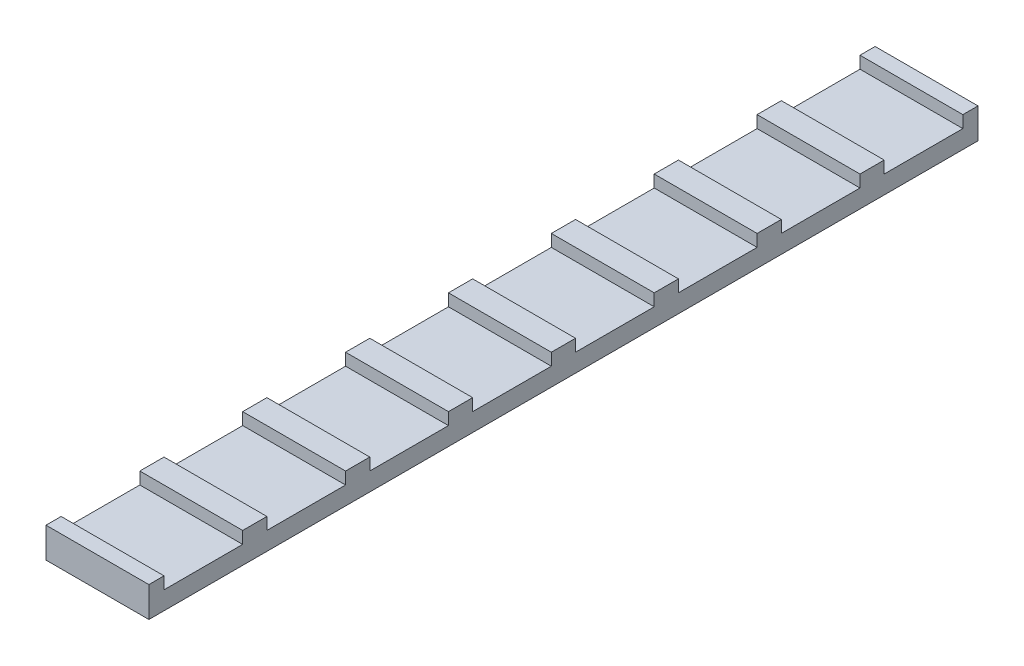
SolidWorks part; units mm, degrees
ref_plane "Front Plane" through (0, 0, 0) normal (0, 0, 1) x (1, 0, 0)
ref_plane "Top Plane" through (0, 0, 0) normal (0, 1, 0) x (1, 0, 0)
ref_plane "Right Plane" through (0, 0, 0) normal (1, 0, 0) x (0, 0, -1)
sketch "Sketch1" plane through (0, 0, 0) normal (0, 1, 0) x (1, 0, 0)
  line L1 (-8.5, -68.5) -> (8.5, -68.5)
  line L2 (-8.5, -68.5) -> (-8.5, 68.5)
  line L3 (-8.5, 68.5) -> (8.5, 68.5)
  line L4 (8.5, -68.5) -> (8.5, 68.5)
  line L5 (-8.5, -68.5) -> (8.5, 68.5) construction
  line L6 (-8.5, 68.5) -> (8.5, -68.5) construction
  point P0 (0, 0)
  dimension "D1" = 137
  dimension "D2" = 17
extrude "Boss-Extrude1" add sketch "Sketch1" along normal blind 5
sketch "Sketch2" plane through (0, 5, 0) normal (0, 1, 0) x (1, 0, 0)
  line L0 (-8.5, 68.5) -> (-8.5, -68.5) construction
  line L1 (-8.5, 66) -> (8.5, 66)
  line L2 (-8.5, 66) -> (-8.5, 53)
  line L3 (-8.5, 53) -> (8.5, 53)
  line L4 (8.5, 66) -> (8.5, 53)
  line L5 (8.5, -68.5) -> (8.5, 68.5) construction
  line L6 (8.5, 68.5) -> (-8.5, 68.5) construction
  dimension "D1" = 2.5
  dimension "D2" = 13
extrude "Cut-Extrude1" cut sketch "Sketch2" against normal blind 2
pattern_linear "LPattern1" count 8 spacing 17 along (0, 0, 1) of "Cut-Extrude1"
